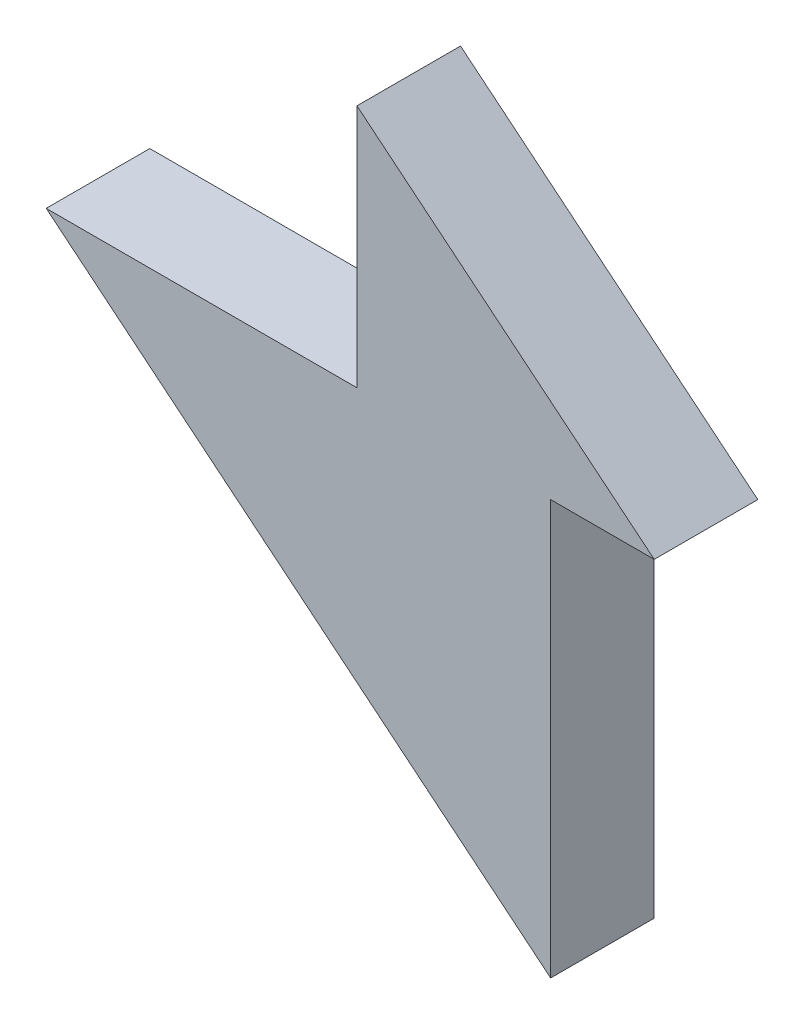
SolidWorks part; units mm, degrees
material "Plain Carbon Steel"
ref_plane "Front Plane" through (0, 0, 0) normal (0, 0, 1) x (1, 0, 0)
ref_plane "Top Plane" through (0, 0, 0) normal (0, 1, 0) x (1, 0, 0)
ref_plane "Right Plane" through (0, 0, 0) normal (1, 0, 0) x (0, 0, -1)
sketch "Sketch1" plane through (0, 0, 0) normal (0, 0, 1) x (1, 0, 0)
  line L0 (0, -10.4) -> (-30.925, 15)
  line L1 (-30.925, 15) -> (-11.875, 15)
  line L2 (-11.875, 15) -> (-11.875, 29.969)
  line L3 (-11.875, 29.969) -> (6.35, 15)
  line L4 (6.35, 15) -> (0, 15)
  line L5 (0, 15) -> (0, -10.4)
  line L6 (-30.925, 16.5503) -> (-30.925, 32.4997) construction
  line L7 (-11.875, 32.4997) -> (-11.875, 16.5503) construction
extrude "Boss-Extrude1" add sketch "Sketch1" against normal blind 6.35 contours L0 L1 L2 L3 L4 L5
